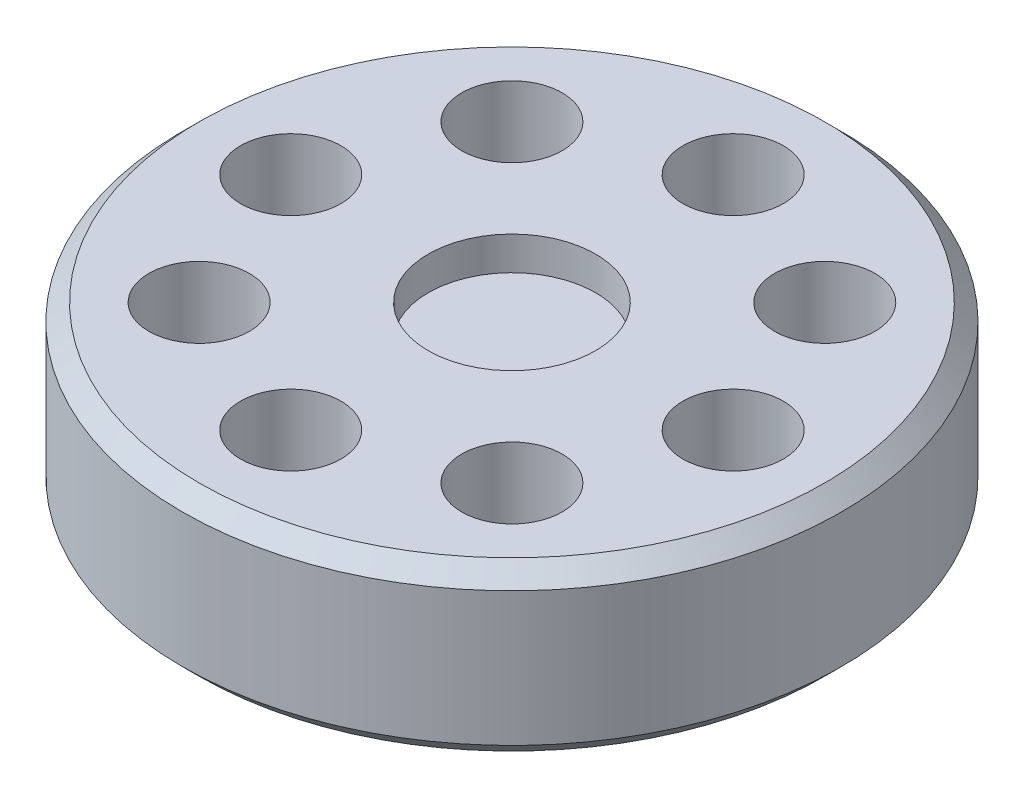
SolidWorks part; units mm, degrees
ref_plane "Front Plane" through (0, 0, 0) normal (0, 0, 1) x (1, 0, 0)
ref_plane "Top Plane" through (0, 0, 0) normal (0, 1, 0) x (1, 0, 0)
ref_plane "Right Plane" through (0, 0, 0) normal (1, 0, 0) x (0, 0, -1)
sketch "Wheel_Circle" plane through (0, 0, 0) normal (0, 1, 0) x (1, 0, 0)
  circle A0 centre (0, 0) radius 50
extrude "Wheel_thick" add sketch "Wheel_Circle" along normal blind 25.4 contours A0
sketch "Sketch2" plane through (0, 25.4, 0) normal (0, 1, 0) x (1, 0, 0)
  circle A0 centre (0, 0) radius 12.7
extrude "Cut-Extrude1" cut sketch "Sketch2" against normal blind 5.08 contours A0
chamfer "Chamfer3" distance 2.54 angle 45 2 edges at (0, 0, 50) (0, 25.4, 50)
sketch "Sketch4" plane through (0, 25.4, 0) normal (0, 1, 0) x (1, 0, 0)
  line L0 (0, 0) -> (0, -47.46)
  line L1 (0, -47.46) -> (0, 47.46)
  line L2 (0, 0) -> (-47.46, 0)
  line L3 (-47.46, 0) -> (47.46, 0)
  line L4 (47.46, 0) -> (0, 47.46)
  line L5 (0, 0) -> (33.5593, 33.5593)
  line L6 (33.5593, 33.5593) -> (-33.5593, -33.5593)
  line L7 (0, 0) -> (33.5593, -33.5593)
  line L8 (33.5593, -33.5593) -> (-33.5593, 33.5593)
  line L9 (0, 47.46) -> (-47.46, 0)
  line L10 (-47.46, 0) -> (0, -47.46)
  line L11 (47.46, 0) -> (0, -47.46)
  line L12 (33.5593, -33.5593) -> (33.5593, 33.5593)
  line L13 (-33.5593, 33.5593) -> (33.5593, 33.5593)
  line L14 (-33.5593, 33.5593) -> (-33.5593, -33.5593)
  line L15 (-33.5593, -33.5593) -> (33.5593, -33.5593)
  circle A0 centre (0, 0) radius 47.46 construction
  circle A1 centre (-33.5593, 0) radius 7.62
  circle A2 centre (-23.73, 23.73) radius 7.62
  circle A3 centre (0, 33.5593) radius 7.62
  circle A4 centre (23.73, 23.73) radius 7.62
  circle A5 centre (33.5593, 0) radius 7.62
  circle A6 centre (23.73, -23.73) radius 7.62
  circle A7 centre (0, -33.5593) radius 7.62
  circle A8 centre (-23.73, -23.73) radius 7.62
  dimension "D1" = 15.24
  dimension "D2" = 15.24
  dimension "D3" = 15.24
  dimension "D4" = 15.24
  dimension "D5" = 15.24
  dimension "D6" = 15.24
  dimension "D7" = 15.24
  dimension "D8" = 15.24
extrude "Cut-Extrude2" cut sketch "Sketch4" against normal through all contours L3 A5 L12 | L12 A5 L3 | L3 A5 L12 | L12 A5 L3 | L8 A6 L11 | L11 A6 L8 | L8 A6 L11 | L11 A6 L8 | L1 A7 L15 | L15 A7 L1 | L1 A7 L15 | L15 A7 L1 | L10 A8 L6 | L6 A8 L10 | L10 A8 L6 | L6 A8 L10 | L14 A1 L3 | L3 A1 L14 | L14 A1 L3 | L3 A1 L14 | L8 A2 L9 | L9 A2 L8 | L8 A2 L9 | L9 A2 L8 | A4 | A3
sketch "Sketch6" plane through (0, 0, 0) normal (1, 0, 0) x (0, 0, -1)
  line L0 (1.4131, 26.5876) -> (1.4131, 0)
